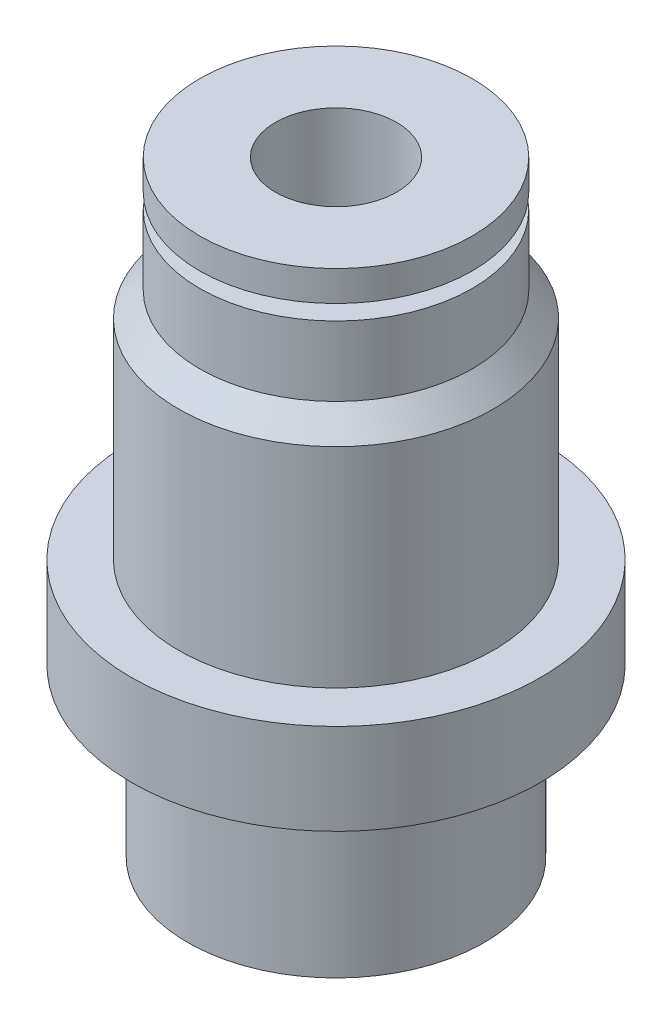
SolidWorks part; units mm, degrees
ref_plane "Спереди" through (0, 0, 0) normal (0, 0, 1) x (1, 0, 0)
ref_plane "Сверху" through (0, 0, 0) normal (0, 1, 0) x (1, 0, 0)
ref_plane "Справа" through (0, 0, 0) normal (1, 0, 0) x (0, 0, -1)
sketch "Эскиз1" plane through (0, 0, 0) normal (0, 0, 1) x (1, 0, 0)
  line L0 (0, 0) -> (0, 27.0123) construction
  line L1 (0, 20) -> (4.5, 20)
  line L2 (4.5, 20) -> (4.5, 19)
  line L3 (4.5, 19) -> (3, 19)
  line L4 (3, 19) -> (3, 18.5)
  line L5 (3, 18.5) -> (4.5, 18.5)
  line L6 (4.5, 18.5) -> (4.5, 16.2)
  line L7 (5.1962, 15.4) -> (5.1962, 8.5)
  line L8 (5.1962, 8.5) -> (6.75, 8.5)
  line L9 (6.75, 8.5) -> (6.75, 5.5)
  line L10 (6.75, 5.5) -> (4.9, 5.5)
  line L11 (4.9, 5.5) -> (4.9, 0)
  line L12 (4.9, 0) -> (0, 0)
  line L13 (2, 20) -> (2, 5.5)
  line L14 (2.1, 0) -> (2.1, 5.5)
  line L15 (2.1, 5.5) -> (2, 5.5)
  line L16 (4.5, 16.2) -> (5.1962, 15.4)
  line L18 (5.1962, 13.5062) -> (2.5981, 18.0062) construction
  line L19 (2.5981, 18.0062) -> (-2.5981, 18.0062) construction
  line L20 (-2.5981, 18.0062) -> (-5.1962, 13.5062) construction
  line L21 (-5.1962, 13.5062) -> (-2.5981, 9.0062) construction
  line L22 (-2.5981, 9.0062) -> (2.5981, 9.0062) construction
  line L23 (2.5981, 9.0062) -> (5.1962, 13.5062) construction
  circle A0 centre (0, 13.5062) radius 4.5 construction
  dimension "D1" = 20
  dimension "D2" = 5.5
  dimension "D3" = 2
  dimension "D4" = 9
  dimension "D5" = 2.1
  dimension "D6" = 1
  dimension "D7" = 2.5
  dimension "D8" = 0.5
  dimension "D9" = 1
  dimension "D10" = 4.6
  dimension "D11" = 0.8
  dimension "D12" = 3
  dimension "D13" = 9.8
  dimension "D14" = 13.5
revolve "Повернуть1" add sketch "Эскиз1" angle 360 about L0
